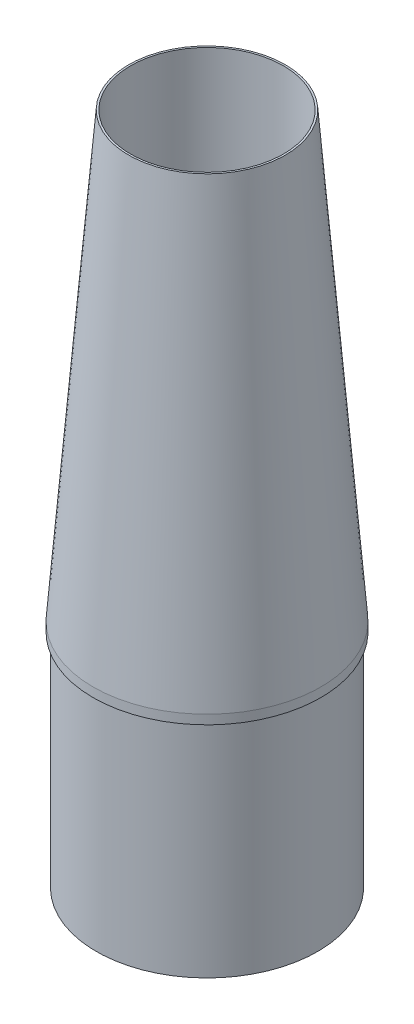
SolidWorks part; units mm, degrees
material "6061 Alloy"
ref_plane "Front Plane" through (0, 0, 0) normal (0, 0, 1) x (1, 0, 0)
ref_plane "Top Plane" through (0, 0, 0) normal (0, 1, 0) x (1, 0, 0)
ref_plane "Right Plane" through (0, 0, 0) normal (1, 0, 0) x (0, 0, -1)
other "Center of Mass" [suppressed]
sketch "Sketch1" plane through (0, 0, 0) normal (0, 0, 1) x (1, 0, 0)
  line L0 (0, 0) -> (-34.925, 0)
  line L1 (-34.925, 0) -> (-34.925, 30.48)
  line L2 (-34.925, 30.48) -> (-52.6542, 30.48)
  line L3 (-52.6542, 30.48) -> (-52.6542, 157.4736)
  line L4 (-53.9242, 157.4736) -> (-78.359, -147.3264)
  line L5 (-78.359, -147.3264) -> (-78.359, -153.6764)
  line L6 (-78.359, -153.6764) -> (-76.2, -153.6764)
  line L7 (-76.2, -153.6764) -> (-76.2, -306.0764)
  line L8 (-76.2, -306.0764) -> (-69.85, -306.0764)
  line L9 (-69.85, -306.0764) -> (-69.85, -136.5419)
  line L10 (-77.4456, -135.933) -> (-69.85, -136.5419) construction
  line L11 (0, -337.711) -> (0, 337.711) construction
  line L12 (0, 0) -> (0, -12.7)
  line L13 (0, -12.7) -> (-38.1, -12.7)
  line L14 (-38.1, -12.7) -> (-61.5209, -32.6444)
  line L15 (-61.5209, -32.6444) -> (-69.85, -136.5419)
  line L16 (-61.5209, -32.6444) -> (-69.1165, -32.0355) construction
  line L17 (-52.6542, 157.4736) -> (-53.9242, 157.4736)
  point P18 (0, 0)
  dimension "D1" = 34.925
  dimension "D2" = 30.48
  dimension "D3" = 52.6542
  dimension "D4" = 127
  dimension "D5" = 78.359
  dimension "D6" = 304.8
  dimension "D7" = 6.35
  dimension "D8" = 2.159
  dimension "D9" = 152.4
  dimension "D10" = 6.35
  dimension "D11" = 7.62
  dimension "D12" = 12.7
  dimension "D13" = 45
  dimension "D14" = 38.1
  dimension "D15" = 1.27
revolve "Revolve1" add sketch "Sketch1" angle 360 about L11
equation "\"CF_OD_A\"= 4.015in"
equation "\"CF_ID_A\"= 3.904in"
equation "\"KF_ID_A\"= 4.015in ' Kevlar airframe ID"
equation "\"CF_OD_C\"= 3.894in ' VERIFY Coupler OD"
equation "\"CF_ID_C\"= 3.783in ' VERIFY Coupler ID"
equation "\"KF_WALL\"= 0.0625in"
equation "\"AF_01\"=62in"
equation "\"AF_02\"=22in"
equation "\"AF_03\"=56in"
equation "\"B_CF_OD\"=6.17in"
equation "\"B_CF_ID\"=6in"
equation "\"B_CF_WT\"=0.085in"
equation "\"B_Fin_Root\"=18in"
equation "\"D3@Sketch1\"=(\"KF_ID_A\" /2) +\"KF_WALL\" + 0.003"
equation "\"D5@Sketch1\"=\"B_CF_OD\" / 2"
equation "\"D8@Sketch1\"=\"B_CF_WT\""
